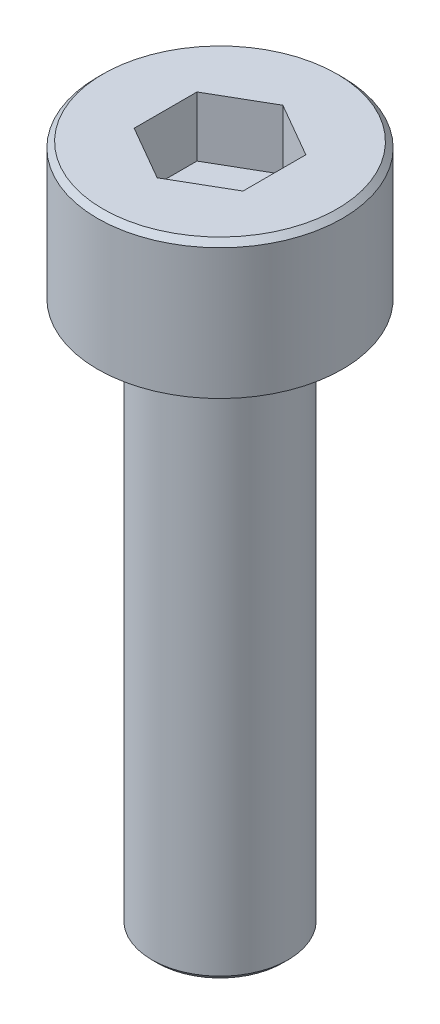
SolidWorks part; units mm, degrees
material "AISI 316, barra ricotta (SS)"
ref_plane "Piano frontale" through (0, 0, 0) normal (0, 0, 1) x (1, 0, 0)
ref_plane "Piano superiore" through (0, 0, 0) normal (0, 1, 0) x (1, 0, 0)
ref_plane "Piano destro" through (0, 0, 0) normal (1, 0, 0) x (0, 0, -1)
sketch "Schizzo1" plane through (0, 0, 0) normal (0, 0, 1) x (1, 0, 0)
  line L0 (0, 0) -> (0, 2.5)
  line L1 (0, 2.5) -> (2.25, 2.5)
  line L2 (2.25, 2.5) -> (2.25, 0)
  line L3 (2.25, 0) -> (1.25, 0)
  line L4 (1.25, 0) -> (1.25, -10)
  line L5 (1.25, -10) -> (0, -10)
  line L6 (0, -10) -> (0, 0)
  line L7 (0, 28.3885) -> (0, -27.6749) construction
  dimension "D1" = 2.5
  dimension "D2" = 2.5
  dimension "D3" = 4.5
  dimension "D4" = 10
revolve "Rivoluzione1" add sketch "Schizzo1" angle 360 about L7
chamfer "Smusso1" distance 0.1 angle 45 2 edges at (0, 2.5, 2.25) (0, -10, 1.25)
sketch "Schizzo2" plane through (0, 2.5, 0) normal (0, 1, 0) x (1, 0, 0)
  line L1 (0, 1.1547) -> (-1, 0.5774)
  line L2 (-1, 0.5774) -> (-1, -0.5774)
  line L3 (-1, -0.5774) -> (0, -1.1547)
  line L4 (0, -1.1547) -> (1, -0.5774)
  line L5 (1, -0.5774) -> (1, 0.5774)
  line L6 (1, 0.5774) -> (0, 1.1547)
  circle A0 centre (0, 0) radius 1 construction
  dimension "D1" = 2
extrude "Taglio-Estrusione1" cut sketch "Schizzo2" against normal blind 1.1
